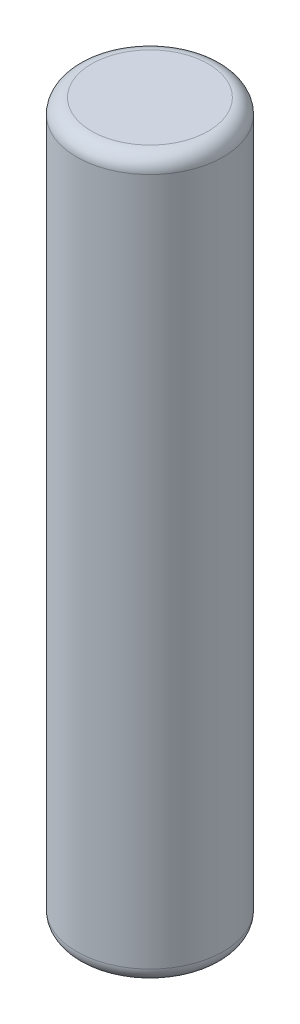
SolidWorks part; units mm, degrees
ref_plane "Front Plane" through (0, 0, 0) normal (0, 0, 1) x (1, 0, 0)
ref_plane "Top Plane" through (0, 0, 0) normal (0, 1, 0) x (1, 0, 0)
ref_plane "Right Plane" through (0, 0, 0) normal (1, 0, 0) x (0, 0, -1)
sketch "Sketch1" plane through (0, 0, 0) normal (0, 1, 0) x (1, 0, 0)
  circle A0 centre (0, 0) radius 2.45
  dimension "D1" = 4.9
extrude "Boss-Extrude1" add sketch "Sketch1" along normal blind 24
fillet "Fillet1" radius 0.5 2 edges at (0, 0, 2.45) (0, 24, 2.45)
